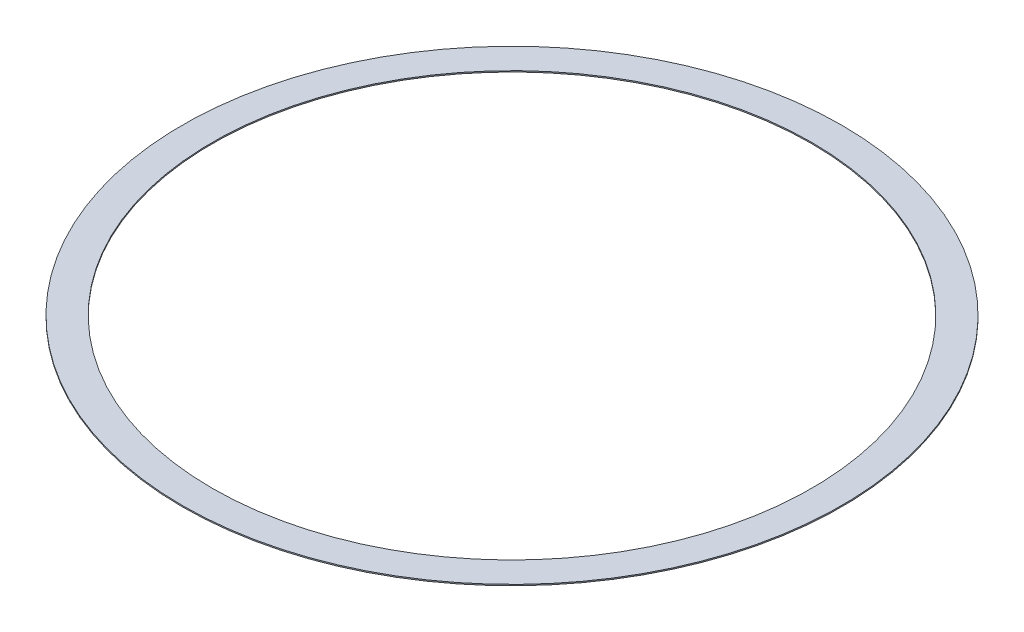
SolidWorks part; units mm, degrees
material "ASTM A36 Steel"
ref_plane "Front Plane" through (0, 0, 0) normal (0, 0, 1) x (1, 0, 0)
ref_plane "Top Plane" through (0, 0, 0) normal (0, 1, 0) x (1, 0, 0)
ref_plane "Right Plane" through (0, 0, 0) normal (1, 0, 0) x (0, 0, -1)
sketch "Sketch1" plane through (0, 0, 0) normal (0, 1, 0) x (1, 0, 0)
  circle A0 centre (0, 0) radius 501.5
  circle A1 centre (0, 0) radius 551.5
  dimension "D1" = 1003
  dimension "D2" = 50
extrude "Boss-Extrude1" add sketch "Sketch1" along normal blind 2
